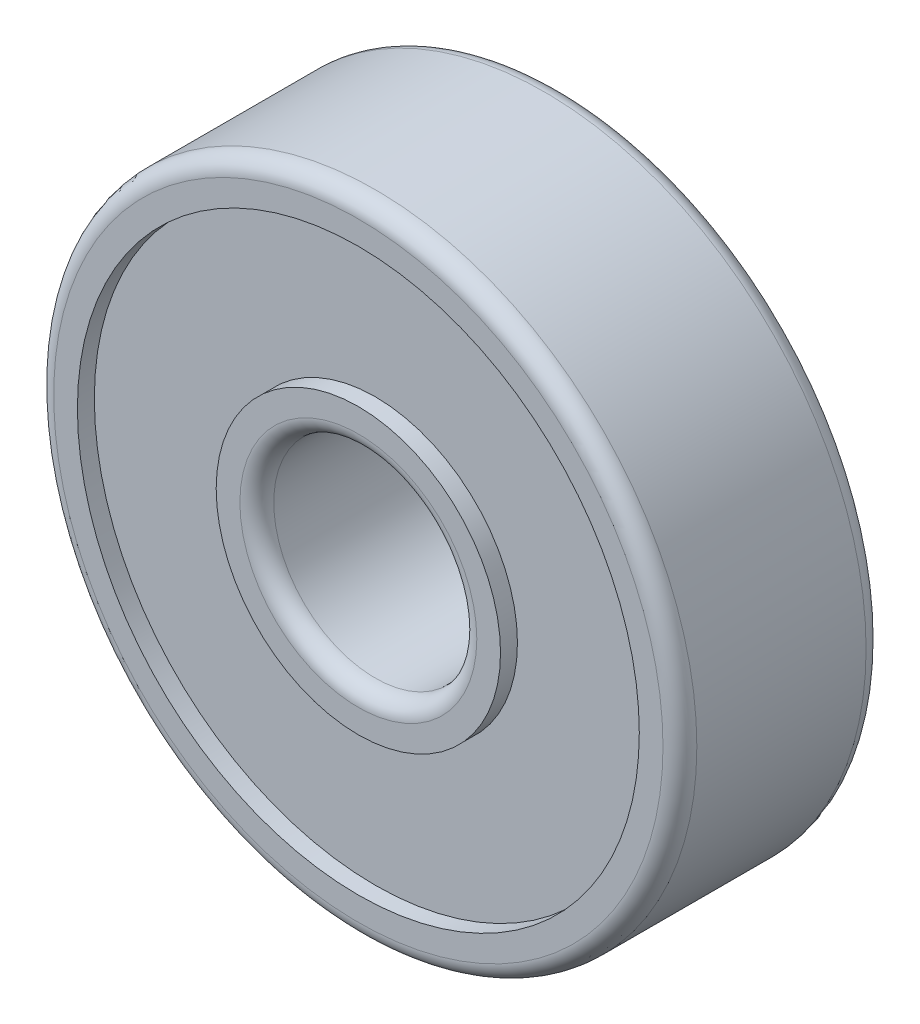
SolidWorks part; units mm, degrees
ref_plane "Plano frontal" through (0, 0, 0) normal (0, 0, 1) x (1, 0, 0)
ref_plane "Plano superior" through (0, 0, 0) normal (0, 1, 0) x (1, 0, 0)
ref_plane "Plano direito" through (0, 0, 0) normal (1, 0, 0) x (0, 0, -1)
sketch "Esboço1" plane through (0, 0, 0) normal (0, 0, 1) x (1, 0, 0)
  circle A0 centre (0, 0) radius 9.5
  circle A1 centre (0, 0) radius 3
  dimension "D1" = 6
  dimension "D2" = 19
extrude "Ressalto-extrusão1" add sketch "Esboço1" along normal blind 6
sketch "Esboço2" plane through (0, 0, 6) normal (0, 0, 1) x (1, 0, 0)
  circle A0 centre (0, 0) radius 4.2
  circle A3 centre (0, 0) radius 3 construction
  circle A4 centre (0, 0) radius 8.3
  circle A5 centre (0, 0) radius 9.5 construction
  dimension "D1" = 1.2
  dimension "D2" = 1.2
extrude "Corte-extrusão1" cut sketch "Esboço2" against normal blind 0.5
sketch "Esboço3" plane through (0, 0, 0) normal (0, 0, -1) x (-1, 0, 0)
  circle A0 centre (0, 0) radius 4.2
  circle A1 centre (0, 0) radius 8.3
  circle A2 centre (0, 0) radius 3 construction
  circle A3 centre (0, 0) radius 9.5 construction
  dimension "D1" = 1.2
  dimension "D2" = 1.2
extrude "Corte-extrusão2" cut sketch "Esboço3" against normal blind 0.5
fillet "Filete1" radius 0.5 4 edges at (9.5, 0, 0) (9.5, 0, 6) (3, 0, 0) (3, 0, 6)
